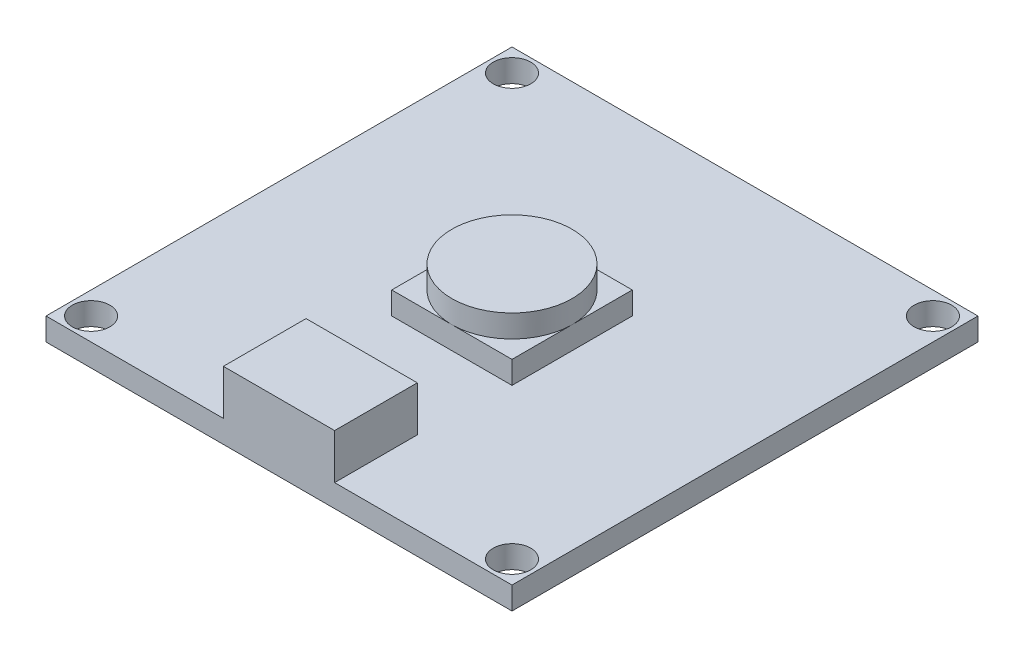
SolidWorks part; units mm, degrees
ref_plane "Front Plane" through (0, 0, 0) normal (0, 0, 1) x (1, 0, 0)
ref_plane "Top Plane" through (0, 0, 0) normal (0, 1, 0) x (1, 0, 0)
ref_plane "Right Plane" through (0, 0, 0) normal (1, 0, 0) x (0, 0, -1)
sketch "Sketch1" plane through (0, 0, 0) normal (0, 1, 0) x (1, 0, 0)
  line L1 (-15.5, -15.5) -> (15.5, -15.5)
  line L2 (-15.5, -15.5) -> (-15.5, 15.5)
  line L3 (-15.5, 15.5) -> (15.5, 15.5)
  line L4 (15.5, -15.5) -> (15.5, 15.5)
  line L5 (-15.5, -15.5) -> (15.5, 15.5) construction
  line L6 (-15.5, 15.5) -> (15.5, -15.5) construction
  point P0 (0, 0)
  dimension "D1" = 31
  dimension "D2" = 31
extrude "Boss-Extrude1" add sketch "Sketch1" along normal blind 1.5
sketch "Sketch2" plane through (0, 1.5, 0) normal (0, 1, 0) x (1, 0, 0)
  line L1 (-4, -4) -> (4, -4)
  line L2 (-4, -4) -> (-4, 4)
  line L3 (-4, 4) -> (4, 4)
  line L4 (4, -4) -> (4, 4)
  line L5 (-4, -4) -> (4, 4) construction
  line L6 (-4, 4) -> (4, -4) construction
  point P0 (0, 0)
  dimension "D1" = 8
  dimension "D2" = 8
extrude "Boss-Extrude2" add sketch "Sketch2" along normal blind 1.5
sketch "Sketch3" plane through (0, 3, 0) normal (0, 1, 0) x (1, 0, 0)
  circle A0 centre (0, 0) radius 4
extrude "Boss-Extrude3" add sketch "Sketch3" along normal blind 1.5
sketch "Sketch4" plane through (0, 1.5, 0) normal (0, 1, 0) x (1, 0, 0)
  line L0 (0, 0) -> (0, 50000) construction
  line L1 (-15.5, -15.5) -> (15.5, -15.5) construction
  line L2 (-3.7, -10) -> (3.7, -10)
  line L3 (-3.7, -10) -> (-3.7, -15.5)
  line L4 (-3.7, -15.5) -> (3.7, -15.5)
  line L5 (3.7, -10) -> (3.7, -15.5)
  line L6 (-3.7, -10) -> (3.7, -15.5) construction
  line L7 (-3.7, -15.5) -> (3.7, -10) construction
  point P3 (0, -12.75)
  dimension "D1" = 7.4
  dimension "D2" = 5.5
extrude "Boss-Extrude4" add sketch "Sketch4" along normal blind 3
sketch "Sketch5" plane through (0, 1.5, 0) normal (0, 1, 0) x (1, 0, 0)
  line L1 (-14, -14) -> (14, -14) construction
  line L2 (-14, -14) -> (-14, 14) construction
  line L3 (-14, 14) -> (14, 14) construction
  line L4 (14, -14) -> (14, 14) construction
  line L5 (-14, -14) -> (14, 14) construction
  line L6 (-14, 14) -> (14, -14) construction
  circle A0 centre (-14, 14) radius 1.25
  circle A1 centre (14, 14) radius 1.25
  circle A2 centre (14, -14) radius 1.25
  circle A3 centre (-14, -14) radius 1.25
  point P0 (0, 0)
  dimension "D1" = 2.5
  dimension "D2" = 28
extrude "Cut-Extrude1" cut sketch "Sketch5" against normal through all
